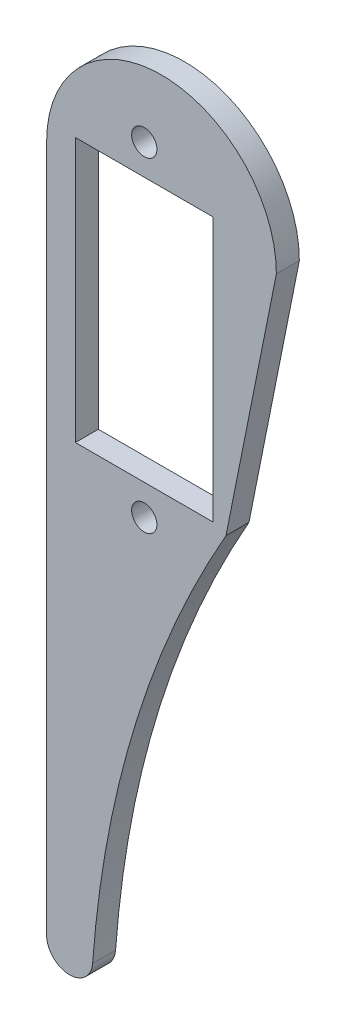
SolidWorks part; units mm, degrees
ref_plane "Front Plane" through (0, 0, 0) normal (0, 0, 1) x (1, 0, 0)
ref_plane "Top Plane" through (0, 0, 0) normal (0, 1, 0) x (1, 0, 0)
ref_plane "Right Plane" through (0, 0, 0) normal (1, 0, 0) x (0, 0, -1)
sketch "Sketch1" plane through (0, 0, 0) normal (0, 0, 1) x (1, 0, 0)
  line L0 (-1.7837, 2.3295) -> (-1.7837, -57.6705)
  line L1 (18.2163, 2.3295) -> (13.8294, -19.6051)
  arc A0 (-1.7837, 2.3295) -> (18.2163, 2.3295) centre (8.2163, 2.3295) cw
  arc A2 (2.2163, -57.6705) -> (-1.7837, -57.6705) centre (0.2163, -57.5218) cw
  spline S0 degree 3 poles (13.8294, -19.6051) (7.0976, -31.4006) (3.2266, -44.0891) (2.2163, -57.6705) knots 0 0 0 0 1 1 1 1
  dimension "D2" = 10
  dimension "D1" = 60
extrude "Boss-Extrude1" add sketch "Sketch1" along normal blind 2
sketch "Sketch2" plane through (0, 0, 2) normal (0, 0, 1) x (1, 0, 0)
  line L1 (0.7163, 3.8606) -> (12.7163, 3.8606)
  line L2 (0.7163, 3.8606) -> (0.7163, -19.1394)
  line L3 (0.7163, -19.1394) -> (12.7163, -19.1394)
  line L4 (12.7163, 3.8606) -> (12.7163, -19.1394)
  line L5 (-1.7837, 2.3295) -> (-1.7837, -57.6705) construction
  circle A0 centre (6.7163, 6.5106) radius 1.1
  circle A1 centre (6.7163, -21.7894) radius 1.1
  dimension "D4" = 2.2
  dimension "D1" = 23
  dimension "D2" = 12
  dimension "D3" = 2.5
  dimension "D5" = 2.65
  dimension "D6" = 2.65
extrude "Cut-Extrude1" cut sketch "Sketch2" against normal up to next
